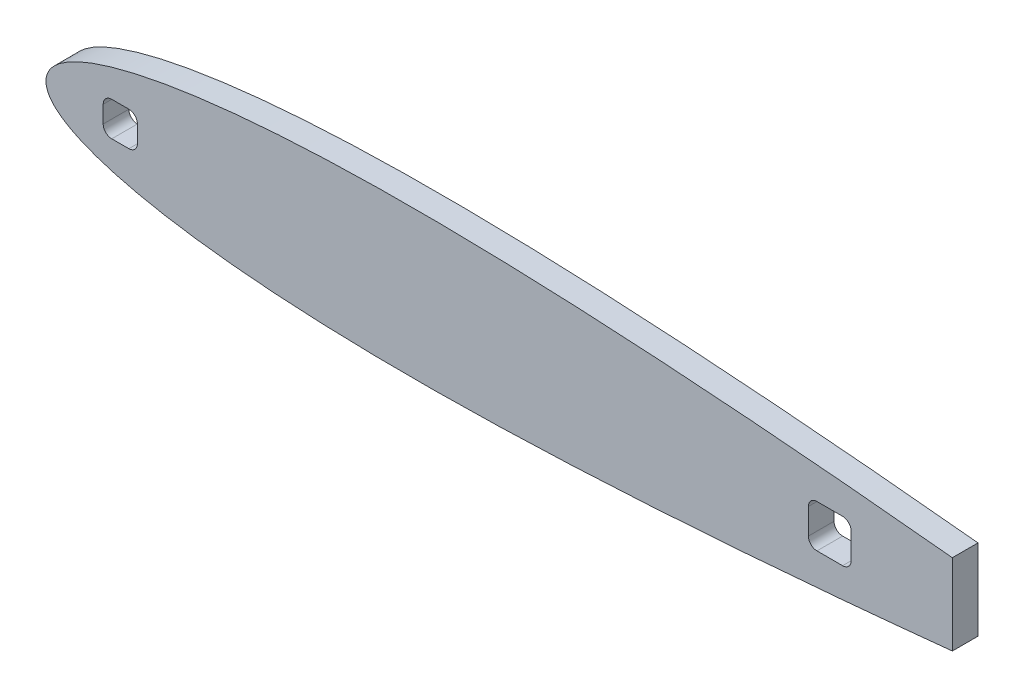
SolidWorks part; units mm, degrees
ref_plane "Plano frontal" through (0, 0, 0) normal (0, 0, 1) x (1, 0, 0)
ref_plane "Plano superior" through (0, 0, 0) normal (0, 1, 0) x (1, 0, 0)
ref_plane "Plano direito" through (0, 0, 0) normal (1, 0, 0) x (0, 0, -1)
curve "2"
  spline degree 3 poles (288.183, -0.2492, 0) (291.6672, 0, 0) (288.183, 0.2492, 0) (287.1244, 0.4014, 0) (286.6168, 0.4717, 0) (285.7832, 0.5886, 0) (284.6138, 0.7512, 0) (283.1169, 0.9577, 0) (281.2938, 1.2084, 0) (279.1495, 1.5004, 0) (276.6888, 1.832, 0) (273.9176, 2.2016, 0) (270.8422, 2.6067, 0) (267.47, 3.0454, 0) (263.8086, 3.5141, 0) (259.8667, 4.0116, 0) (255.6534, 4.5345, 0) (251.1787, 5.08, 0) (246.453, 5.6458, 0) (241.4874, 6.2288, 0) (236.2932, 6.8256, 0) (230.8828, 7.4346, 0) (225.2688, 8.0516, 0) (219.4645, 8.6747, 0) (213.483, 9.2996, 0) (207.3387, 9.9251, 0) (201.0457, 10.5464, 0) (194.6188, 11.1616, 0) (188.0729, 11.7663, 0) (181.4234, 12.3586, 0) (174.6858, 12.9335, 0) (167.8757, 13.4886, 0) (161.0093, 14.0203, 0) (154.1024, 14.5243, 0) (147.1712, 14.9974, 0) (140.232, 15.4359, 0) (133.3008, 15.8355, 0) (126.394, 16.193, 0) (119.5274, 16.5047, 0) (112.7172, 16.7669, 0) (105.9794, 16.9769, 0) (99.3298, 17.1307, 0) (92.7837, 17.2258, 0) (86.3563, 17.2595, 0) (80.0629, 17.2297, 0) (73.918, 17.1352, 0) (67.9362, 16.973, 0) (62.1311, 16.7439, 0) (56.5165, 16.4463, 0) (51.1054, 16.0809, 0) (45.9104, 15.6479, 0) (40.9437, 15.148, 0) (36.2169, 14.5831, 0) (31.7407, 13.9556, 0) (27.5258, 13.2665, 0) (23.5819, 12.5195, 0) (19.9179, 11.7171, 0) (16.5425, 10.8622, 0) (13.4631, 9.9587, 0) (10.6866, 9.0094, 0) (8.2187, 8.0177, 0) (6.0645, 6.9865, 0) (4.228, 5.9178, 0) (2.7114, 4.8135, 0) (1.5175, 3.6719, 0) (0.6493, 2.4895, 0) (0.1185, 1.2608, 0) (-0.0578, 0, 0) (0.1185, -1.2608, 0) (0.6493, -2.4895, 0) (1.5175, -3.6719, 0) (2.7114, -4.8135, 0) (4.228, -5.9178, 0) (6.0645, -6.9865, 0) (8.2187, -8.0177, 0) (10.6866, -9.0094, 0) (13.4631, -9.9587, 0) (16.5425, -10.8622, 0) (19.9179, -11.7171, 0) (23.5819, -12.5195, 0) (27.5258, -13.2665, 0) (31.7407, -13.9556, 0) (36.2169, -14.5831, 0) (40.9437, -15.148, 0) (45.9104, -15.6479, 0) (51.1054, -16.0809, 0) (56.5165, -16.4463, 0) (62.1311, -16.7439, 0) (67.9362, -16.973, 0) (73.918, -17.1352, 0) (80.0629, -17.2297, 0) (86.3563, -17.2595, 0) (92.7837, -17.2258, 0) (99.3298, -17.1307, 0) (105.9794, -16.9769, 0) (112.7172, -16.7669, 0) (119.5274, -16.5047, 0) (126.394, -16.193, 0) (133.3008, -15.8355, 0) (140.232, -15.4359, 0) (147.1712, -14.9974, 0) (154.1024, -14.5243, 0) (161.0093, -14.0203, 0) (167.8757, -13.4886, 0) (174.6858, -12.9335, 0) (181.4234, -12.3586, 0) (188.0729, -11.7663, 0) (194.6188, -11.1616, 0) (201.0457, -10.5464, 0) (207.3387, -9.9251, 0) (213.483, -9.2996, 0) (219.4645, -8.6747, 0) (225.2688, -8.0516, 0) (230.8828, -7.4346, 0) (236.2932, -6.8256, 0) (241.4874, -6.2288, 0) (246.453, -5.6458, 0) (251.1787, -5.08, 0) (255.6534, -4.5345, 0) (259.8667, -4.0116, 0) (263.8086, -3.5141, 0) (267.47, -3.0454, 0) (270.8422, -2.6067, 0) (273.9176, -2.2016, 0) (276.6888, -1.832, 0) (279.1495, -1.5004, 0) (281.2938, -1.2084, 0) (283.1169, -0.9577, 0) (284.6138, -0.7512, 0) (285.7832, -0.5886, 0) (286.6168, -0.4717, 0) (287.1244, -0.4014, 0) (288.183, -0.2492, 0) (291.6672, 0, 0) (288.183, 0.2492, 0) knots -0.00555 -0.004691 -0.004405 0 0.004405 0.004691 0.00555 0.00698 0.008976 0.011535 0.014649 0.018312 0.022515 0.027248 0.032498 0.038254 0.044502 0.051227 0.058413 0.066043 0.074099 0.082562 0.091412 0.100627 0.110187 0.120068 0.130247 0.140701 0.151404 0.162332 0.173459 0.184758 0.196204 0.207769 0.219426 0.231148 0.242906 0.254675 0.266426 0.278132 0.289766 0.301302 0.312712 0.323969 0.33505 0.345929 0.356581 0.366982 0.37711 0.386942 0.396458 0.405637 0.414459 0.422907 0.430963 0.438612 0.445838 0.45263 0.458976 0.464866 0.470294 0.475255 0.479749 0.483781 0.487363 0.490516 0.493279 0.495712 0.49791 0.5 0.50209 0.504288 0.506721 0.509484 0.512637 0.516219 0.520251 0.524745 0.529706 0.535134 0.541024 0.54737 0.554162 0.561388 0.569037 0.577093 0.585541 0.594363 0.603542 0.613058 0.62289 0.633018 0.643419 0.654071 0.66495 0.676031 0.687288 0.698698 0.710234 0.721868 0.733574 0.745325 0.757094 0.768852 0.780574 0.792231 0.803796 0.815242 0.826541 0.837668 0.848596 0.859299 0.869753 0.879932 0.889813 0.899373 0.908588 0.917438 0.925901 0.933957 0.941587 0.948773 0.955498 0.961746 0.967502 0.972752 0.977485 0.981688 0.985351 0.988465 0.991024 0.99302 0.99445 0.995309 0.995595 1 1.004405 1.004691 1.00555 periodic
curve "3"
  spline degree 3 poles (285.8178, -0.2472, 0) (289.2733, 0, 0) (285.8178, 0.2472, 0) (284.7679, 0.3981, 0) (284.2644, 0.4678, 0) (283.4377, 0.5838, 0) (282.2778, 0.7451, 0) (280.7932, 0.9499, 0) (278.9851, 1.1985, 0) (276.8584, 1.4881, 0) (274.4179, 1.8169, 0) (271.6694, 2.1836, 0) (268.6193, 2.5853, 0) (265.2747, 3.0204, 0) (261.6434, 3.4852, 0) (257.7338, 3.9787, 0) (253.5551, 4.4973, 0) (249.1172, 5.0383, 0) (244.4303, 5.5995, 0) (239.5054, 6.1777, 0) (234.3538, 6.7696, 0) (228.9879, 7.3736, 0) (223.4199, 7.9855, 0) (217.6632, 8.6035, 0) (211.7309, 9.2233, 0) (205.637, 9.8437, 0) (199.3956, 10.4599, 0) (193.0214, 11.07, 0) (186.5293, 11.6697, 0) (179.9344, 12.2571, 0) (173.2521, 12.8274, 0) (166.4979, 13.3779, 0) (159.6878, 13.9052, 0) (152.8376, 14.4051, 0) (145.9633, 14.8743, 0) (139.0811, 15.3092, 0) (132.2068, 15.7055, 0) (125.3566, 16.0601, 0) (118.5464, 16.3692, 0) (111.7921, 16.6293, 0) (105.1096, 16.8375, 0) (98.5145, 16.9901, 0) (92.0222, 17.0845, 0) (85.6476, 17.1179, 0) (79.4058, 17.0883, 0) (73.3113, 16.9946, 0) (67.3786, 16.8337, 0) (61.6212, 16.6065, 0) (56.0527, 16.3113, 0) (50.6859, 15.9489, 0) (45.5336, 15.5194, 0) (40.6077, 15.0237, 0) (35.9196, 14.4634, 0) (31.4802, 13.841, 0) (27.2999, 13.1577, 0) (23.3883, 12.4167, 0) (19.7544, 11.6209, 0) (16.4067, 10.7731, 0) (13.3526, 9.8769, 0) (10.5989, 8.9355, 0) (8.1513, 7.9519, 0) (6.0147, 6.9291, 0) (4.1933, 5.8692, 0) (2.6891, 4.774, 0) (1.5051, 3.6417, 0) (0.644, 2.4691, 0) (0.1176, 1.2504, 0) (-0.0573, 0, 0) (0.1176, -1.2504, 0) (0.644, -2.4691, 0) (1.5051, -3.6417, 0) (2.6891, -4.774, 0) (4.1933, -5.8692, 0) (6.0147, -6.9291, 0) (8.1513, -7.9519, 0) (10.5989, -8.9355, 0) (13.3526, -9.8769, 0) (16.4067, -10.7731, 0) (19.7544, -11.6209, 0) (23.3883, -12.4167, 0) (27.2999, -13.1577, 0) (31.4802, -13.841, 0) (35.9196, -14.4634, 0) (40.6077, -15.0237, 0) (45.5336, -15.5194, 0) (50.6859, -15.9489, 0) (56.0527, -16.3113, 0) (61.6212, -16.6065, 0) (67.3786, -16.8337, 0) (73.3113, -16.9946, 0) (79.4058, -17.0883, 0) (85.6476, -17.1179, 0) (92.0222, -17.0845, 0) (98.5145, -16.9901, 0) (105.1096, -16.8375, 0) (111.7921, -16.6293, 0) (118.5464, -16.3692, 0) (125.3566, -16.0601, 0) (132.2068, -15.7055, 0) (139.0811, -15.3092, 0) (145.9633, -14.8743, 0) (152.8376, -14.4051, 0) (159.6878, -13.9052, 0) (166.4979, -13.3779, 0) (173.2521, -12.8274, 0) (179.9344, -12.2571, 0) (186.5293, -11.6697, 0) (193.0214, -11.07, 0) (199.3956, -10.4599, 0) (205.637, -9.8437, 0) (211.7309, -9.2233, 0) (217.6632, -8.6035, 0) (223.4199, -7.9855, 0) (228.9879, -7.3736, 0) (234.3538, -6.7696, 0) (239.5054, -6.1777, 0) (244.4303, -5.5995, 0) (249.1172, -5.0383, 0) (253.5551, -4.4973, 0) (257.7338, -3.9787, 0) (261.6434, -3.4852, 0) (265.2747, -3.0204, 0) (268.6193, -2.5853, 0) (271.6694, -2.1836, 0) (274.4179, -1.8169, 0) (276.8584, -1.4881, 0) (278.9851, -1.1985, 0) (280.7932, -0.9499, 0) (282.2778, -0.7451, 0) (283.4377, -0.5838, 0) (284.2644, -0.4678, 0) (284.7679, -0.3981, 0) (285.8178, -0.2472, 0) (289.2733, 0, 0) (285.8178, 0.2472, 0) knots -0.00555 -0.004691 -0.004405 0 0.004405 0.004691 0.00555 0.00698 0.008976 0.011535 0.014649 0.018312 0.022515 0.027248 0.032498 0.038254 0.044502 0.051227 0.058413 0.066043 0.074099 0.082562 0.091412 0.100627 0.110187 0.120068 0.130247 0.140701 0.151404 0.162332 0.173459 0.184758 0.196204 0.207769 0.219426 0.231148 0.242906 0.254675 0.266426 0.278132 0.289766 0.301302 0.312712 0.323969 0.33505 0.345929 0.356581 0.366982 0.37711 0.386942 0.396458 0.405637 0.414459 0.422907 0.430963 0.438612 0.445838 0.45263 0.458976 0.464866 0.470294 0.475255 0.479749 0.483781 0.487363 0.490516 0.493279 0.495712 0.49791 0.5 0.50209 0.504288 0.506721 0.509484 0.512637 0.516219 0.520251 0.524745 0.529706 0.535134 0.541024 0.54737 0.554162 0.561388 0.569037 0.577093 0.585541 0.594363 0.603542 0.613058 0.62289 0.633018 0.643419 0.654071 0.66495 0.676031 0.687288 0.698698 0.710234 0.721868 0.733574 0.745325 0.757094 0.768852 0.780574 0.792231 0.803796 0.815242 0.826541 0.837668 0.848596 0.859299 0.869753 0.879932 0.889813 0.899373 0.908588 0.917438 0.925901 0.933957 0.941587 0.948773 0.955498 0.961746 0.967502 0.972752 0.977485 0.981688 0.985351 0.988465 0.991024 0.99302 0.99445 0.995309 0.995595 1 1.004405 1.004691 1.00555 periodic
sketch "2-3" plane through (0, 0, 0) normal (0, 0, 1) x (1, 0, 0)
  line L0 (287.6, 0) -> (289.98, 0) construction
  spline S0 degree 3 poles (285.8178, -0.2472) (289.2733, 0) (285.8178, 0.2472) (284.7679, 0.3981) (284.2644, 0.4678) (283.4377, 0.5838) (282.2778, 0.7451) (280.7932, 0.9499) (278.9851, 1.1985) (276.8584, 1.4881) (274.4179, 1.8169) (271.6694, 2.1836) (268.6193, 2.5853) (265.2747, 3.0204) (261.6434, 3.4852) (257.7338, 3.9787) (253.5551, 4.4973) (249.1172, 5.0383) (244.4303, 5.5995) (239.5054, 6.1777) (234.3538, 6.7696) (228.9879, 7.3736) (223.4199, 7.9855) (217.6632, 8.6035) (211.7309, 9.2233) (205.637, 9.8437) (199.3956, 10.4599) (193.0214, 11.07) (186.5293, 11.6697) (179.9344, 12.2571) (173.2521, 12.8274) (166.4979, 13.3779) (159.6878, 13.9052) (152.8376, 14.4051) (145.9633, 14.8743) (139.0811, 15.3092) (132.2068, 15.7055) (125.3566, 16.0601) (118.5464, 16.3692) (111.7921, 16.6293) (105.1096, 16.8375) (98.5145, 16.9901) (92.0222, 17.0845) (85.6476, 17.1179) (79.4058, 17.0883) (73.3113, 16.9946) (67.3786, 16.8337) (61.6212, 16.6065) (56.0527, 16.3113) (50.6859, 15.9489) (45.5336, 15.5194) (40.6077, 15.0237) (35.9196, 14.4634) (31.4802, 13.841) (27.2999, 13.1577) (23.3883, 12.4167) (19.7544, 11.6209) (16.4067, 10.7731) (13.3526, 9.8769) (10.5989, 8.9355) (8.1513, 7.9519) (6.0147, 6.9291) (4.1933, 5.8692) (2.6891, 4.774) (1.5051, 3.6417) (0.644, 2.4691) (0.1176, 1.2504) (-0.0573, 0) (0.1176, -1.2504) (0.644, -2.4691) (1.5051, -3.6417) (2.6891, -4.774) (4.1933, -5.8692) (6.0147, -6.9291) (8.1513, -7.9519) (10.5989, -8.9355) (13.3526, -9.8769) (16.4067, -10.7731) (19.7544, -11.6209) (23.3883, -12.4167) (27.2999, -13.1577) (31.4802, -13.841) (35.9196, -14.4634) (40.6077, -15.0237) (45.5336, -15.5194) (50.6859, -15.9489) (56.0527, -16.3113) (61.6212, -16.6065) (67.3786, -16.8337) (73.3113, -16.9946) (79.4058, -17.0883) (85.6476, -17.1179) (92.0222, -17.0845) (98.5145, -16.9901) (105.1096, -16.8375) (111.7921, -16.6293) (118.5464, -16.3692) (125.3566, -16.0601) (132.2068, -15.7055) (139.0811, -15.3092) (145.9633, -14.8743) (152.8376, -14.4051) (159.6878, -13.9052) (166.4979, -13.3779) (173.2521, -12.8274) (179.9344, -12.2571) (186.5293, -11.6697) (193.0214, -11.07) (199.3956, -10.4599) (205.637, -9.8437) (211.7309, -9.2233) (217.6632, -8.6035) (223.4199, -7.9855) (228.9879, -7.3736) (234.3538, -6.7696) (239.5054, -6.1777) (244.4303, -5.5995) (249.1172, -5.0383) (253.5551, -4.4973) (257.7338, -3.9787) (261.6434, -3.4852) (265.2747, -3.0204) (268.6193, -2.5853) (271.6694, -2.1836) (274.4179, -1.8169) (276.8584, -1.4881) (278.9851, -1.1985) (280.7932, -0.9499) (282.2778, -0.7451) (283.4377, -0.5838) (284.2644, -0.4678) (284.7679, -0.3981) (285.8178, -0.2472) (289.2733, 0) (285.8178, 0.2472) knots -0.00555 -0.004691 -0.004405 0 0.004405 0.004691 0.00555 0.00698 0.008976 0.011535 0.014649 0.018312 0.022515 0.027248 0.032498 0.038254 0.044502 0.051227 0.058413 0.066043 0.074099 0.082562 0.091412 0.100627 0.110187 0.120068 0.130247 0.140701 0.151404 0.162332 0.173459 0.184758 0.196204 0.207769 0.219426 0.231148 0.242906 0.254675 0.266426 0.278132 0.289766 0.301302 0.312712 0.323969 0.33505 0.345929 0.356581 0.366982 0.37711 0.386942 0.396458 0.405637 0.414459 0.422907 0.430963 0.438612 0.445838 0.45263 0.458976 0.464866 0.470294 0.475255 0.479749 0.483781 0.487363 0.490516 0.493279 0.495712 0.49791 0.5 0.50209 0.504288 0.506721 0.509484 0.512637 0.516219 0.520251 0.524745 0.529706 0.535134 0.541024 0.54737 0.554162 0.561388 0.569037 0.577093 0.585541 0.594363 0.603542 0.613058 0.62289 0.633018 0.643419 0.654071 0.66495 0.676031 0.687288 0.698698 0.710234 0.721868 0.733574 0.745325 0.757094 0.768852 0.780574 0.792231 0.803796 0.815242 0.826541 0.837668 0.848596 0.859299 0.869753 0.879932 0.889813 0.899373 0.908588 0.917438 0.925901 0.933957 0.941587 0.948773 0.955498 0.961746 0.967502 0.972752 0.977485 0.981688 0.985351 0.988465 0.991024 0.99302 0.99445 0.995309 0.995595 1 1.004405 1.004691 1.00555 only from (287.6, 0) to (287.6, 0) construction
  spline S1 degree 3 poles (288.183, -0.2492) (291.6672, 0) (288.183, 0.2492) (287.1244, 0.4014) (286.6168, 0.4717) (285.7832, 0.5886) (284.6138, 0.7512) (283.1169, 0.9577) (281.2938, 1.2084) (279.1495, 1.5004) (276.6888, 1.832) (273.9176, 2.2016) (270.8422, 2.6067) (267.47, 3.0454) (263.8086, 3.5141) (259.8667, 4.0116) (255.6534, 4.5345) (251.1787, 5.08) (246.453, 5.6458) (241.4874, 6.2288) (236.2932, 6.8256) (230.8828, 7.4346) (225.2688, 8.0516) (219.4645, 8.6747) (213.483, 9.2996) (207.3387, 9.9251) (201.0457, 10.5464) (194.6188, 11.1616) (188.0729, 11.7663) (181.4234, 12.3586) (174.6858, 12.9335) (167.8757, 13.4886) (161.0093, 14.0203) (154.1024, 14.5243) (147.1712, 14.9974) (140.232, 15.4359) (133.3008, 15.8355) (126.394, 16.193) (119.5274, 16.5047) (112.7172, 16.7669) (105.9794, 16.9769) (99.3298, 17.1307) (92.7837, 17.2258) (86.3563, 17.2595) (80.0629, 17.2297) (73.918, 17.1352) (67.9362, 16.973) (62.1311, 16.7439) (56.5165, 16.4463) (51.1054, 16.0809) (45.9104, 15.6479) (40.9437, 15.148) (36.2169, 14.5831) (31.7407, 13.9556) (27.5258, 13.2665) (23.5819, 12.5195) (19.9179, 11.7171) (16.5425, 10.8622) (13.4631, 9.9587) (10.6866, 9.0094) (8.2187, 8.0177) (6.0645, 6.9865) (4.228, 5.9178) (2.7114, 4.8135) (1.5175, 3.6719) (0.6493, 2.4895) (0.1185, 1.2608) (-0.0578, 0) (0.1185, -1.2608) (0.6493, -2.4895) (1.5175, -3.6719) (2.7114, -4.8135) (4.228, -5.9178) (6.0645, -6.9865) (8.2187, -8.0177) (10.6866, -9.0094) (13.4631, -9.9587) (16.5425, -10.8622) (19.9179, -11.7171) (23.5819, -12.5195) (27.5258, -13.2665) (31.7407, -13.9556) (36.2169, -14.5831) (40.9437, -15.148) (45.9104, -15.6479) (51.1054, -16.0809) (56.5165, -16.4463) (62.1311, -16.7439) (67.9362, -16.973) (73.918, -17.1352) (80.0629, -17.2297) (86.3563, -17.2595) (92.7837, -17.2258) (99.3298, -17.1307) (105.9794, -16.9769) (112.7172, -16.7669) (119.5274, -16.5047) (126.394, -16.193) (133.3008, -15.8355) (140.232, -15.4359) (147.1712, -14.9974) (154.1024, -14.5243) (161.0093, -14.0203) (167.8757, -13.4886) (174.6858, -12.9335) (181.4234, -12.3586) (188.0729, -11.7663) (194.6188, -11.1616) (201.0457, -10.5464) (207.3387, -9.9251) (213.483, -9.2996) (219.4645, -8.6747) (225.2688, -8.0516) (230.8828, -7.4346) (236.2932, -6.8256) (241.4874, -6.2288) (246.453, -5.6458) (251.1787, -5.08) (255.6534, -4.5345) (259.8667, -4.0116) (263.8086, -3.5141) (267.47, -3.0454) (270.8422, -2.6067) (273.9176, -2.2016) (276.6888, -1.832) (279.1495, -1.5004) (281.2938, -1.2084) (283.1169, -0.9577) (284.6138, -0.7512) (285.7832, -0.5886) (286.6168, -0.4717) (287.1244, -0.4014) (288.183, -0.2492) (291.6672, 0) (288.183, 0.2492) knots -0.00555 -0.004691 -0.004405 0 0.004405 0.004691 0.00555 0.00698 0.008976 0.011535 0.014649 0.018312 0.022515 0.027248 0.032498 0.038254 0.044502 0.051227 0.058413 0.066043 0.074099 0.082562 0.091412 0.100627 0.110187 0.120068 0.130247 0.140701 0.151404 0.162332 0.173459 0.184758 0.196204 0.207769 0.219426 0.231148 0.242906 0.254675 0.266426 0.278132 0.289766 0.301302 0.312712 0.323969 0.33505 0.345929 0.356581 0.366982 0.37711 0.386942 0.396458 0.405637 0.414459 0.422907 0.430963 0.438612 0.445838 0.45263 0.458976 0.464866 0.470294 0.475255 0.479749 0.483781 0.487363 0.490516 0.493279 0.495712 0.49791 0.5 0.50209 0.504288 0.506721 0.509484 0.512637 0.516219 0.520251 0.524745 0.529706 0.535134 0.541024 0.54737 0.554162 0.561388 0.569037 0.577093 0.585541 0.594363 0.603542 0.613058 0.62289 0.633018 0.643419 0.654071 0.66495 0.676031 0.687288 0.698698 0.710234 0.721868 0.733574 0.745325 0.757094 0.768852 0.780574 0.792231 0.803796 0.815242 0.826541 0.837668 0.848596 0.859299 0.869753 0.879932 0.889813 0.899373 0.908588 0.917438 0.925901 0.933957 0.941587 0.948773 0.955498 0.961746 0.967502 0.972752 0.977485 0.981688 0.985351 0.988465 0.991024 0.99302 0.99445 0.995309 0.995595 1 1.004405 1.004691 1.00555 only from (289.98, 0) to (289.98, 0) construction
  spline S2 degree 3 poles (285.8178, -0.2472) (289.2733, 0) (285.8178, 0.2472) (284.7679, 0.3981) (284.2644, 0.4678) (283.4377, 0.5838) (282.2778, 0.7451) (280.7932, 0.9499) (278.9851, 1.1985) (276.8584, 1.4881) (274.4179, 1.8169) (271.6694, 2.1836) (268.6193, 2.5853) (265.2747, 3.0204) (261.6434, 3.4852) (257.7338, 3.9787) (253.5551, 4.4973) (249.1172, 5.0383) (244.4303, 5.5995) (239.5054, 6.1777) (234.3538, 6.7696) (228.9879, 7.3736) (223.4199, 7.9855) (217.6632, 8.6035) (211.7309, 9.2233) (205.637, 9.8437) (199.3956, 10.4599) (193.0214, 11.07) (186.5293, 11.6697) (179.9344, 12.2571) (173.2521, 12.8274) (166.4979, 13.3779) (159.6878, 13.9052) (152.8376, 14.4051) (145.9633, 14.8743) (139.0811, 15.3092) (132.2068, 15.7055) (125.3566, 16.0601) (118.5464, 16.3692) (111.7921, 16.6293) (105.1096, 16.8375) (98.5145, 16.9901) (92.0222, 17.0845) (85.6476, 17.1179) (79.4058, 17.0883) (73.3113, 16.9946) (67.3786, 16.8337) (61.6212, 16.6065) (56.0527, 16.3113) (50.6859, 15.9489) (45.5336, 15.5194) (40.6077, 15.0237) (35.9196, 14.4634) (31.4802, 13.841) (27.2999, 13.1577) (23.3883, 12.4167) (19.7544, 11.6209) (16.4067, 10.7731) (13.3526, 9.8769) (10.5989, 8.9355) (8.1513, 7.9519) (6.0147, 6.9291) (4.1933, 5.8692) (2.6891, 4.774) (1.5051, 3.6417) (0.644, 2.4691) (0.1176, 1.2504) (-0.0573, 0) (0.1176, -1.2504) (0.644, -2.4691) (1.5051, -3.6417) (2.6891, -4.774) (4.1933, -5.8692) (6.0147, -6.9291) (8.1513, -7.9519) (10.5989, -8.9355) (13.3526, -9.8769) (16.4067, -10.7731) (19.7544, -11.6209) (23.3883, -12.4167) (27.2999, -13.1577) (31.4802, -13.841) (35.9196, -14.4634) (40.6077, -15.0237) (45.5336, -15.5194) (50.6859, -15.9489) (56.0527, -16.3113) (61.6212, -16.6065) (67.3786, -16.8337) (73.3113, -16.9946) (79.4058, -17.0883) (85.6476, -17.1179) (92.0222, -17.0845) (98.5145, -16.9901) (105.1096, -16.8375) (111.7921, -16.6293) (118.5464, -16.3692) (125.3566, -16.0601) (132.2068, -15.7055) (139.0811, -15.3092) (145.9633, -14.8743) (152.8376, -14.4051) (159.6878, -13.9052) (166.4979, -13.3779) (173.2521, -12.8274) (179.9344, -12.2571) (186.5293, -11.6697) (193.0214, -11.07) (199.3956, -10.4599) (205.637, -9.8437) (211.7309, -9.2233) (217.6632, -8.6035) (223.4199, -7.9855) (228.9879, -7.3736) (234.3538, -6.7696) (239.5054, -6.1777) (244.4303, -5.5995) (249.1172, -5.0383) (253.5551, -4.4973) (257.7338, -3.9787) (261.6434, -3.4852) (265.2747, -3.0204) (268.6193, -2.5853) (271.6694, -2.1836) (274.4179, -1.8169) (276.8584, -1.4881) (278.9851, -1.1985) (280.7932, -0.9499) (282.2778, -0.7451) (283.4377, -0.5838) (284.2644, -0.4678) (284.7679, -0.3981) (285.8178, -0.2472) (289.2733, 0) (285.8178, 0.2472) knots -0.00555 -0.004691 -0.004405 0 0.004405 0.004691 0.00555 0.00698 0.008976 0.011535 0.014649 0.018312 0.022515 0.027248 0.032498 0.038254 0.044502 0.051227 0.058413 0.066043 0.074099 0.082562 0.091412 0.100627 0.110187 0.120068 0.130247 0.140701 0.151404 0.162332 0.173459 0.184758 0.196204 0.207769 0.219426 0.231148 0.242906 0.254675 0.266426 0.278132 0.289766 0.301302 0.312712 0.323969 0.33505 0.345929 0.356581 0.366982 0.37711 0.386942 0.396458 0.405637 0.414459 0.422907 0.430963 0.438612 0.445838 0.45263 0.458976 0.464866 0.470294 0.475255 0.479749 0.483781 0.487363 0.490516 0.493279 0.495712 0.49791 0.5 0.50209 0.504288 0.506721 0.509484 0.512637 0.516219 0.520251 0.524745 0.529706 0.535134 0.541024 0.54737 0.554162 0.561388 0.569037 0.577093 0.585541 0.594363 0.603542 0.613058 0.62289 0.633018 0.643419 0.654071 0.66495 0.676031 0.687288 0.698698 0.710234 0.721868 0.733574 0.745325 0.757094 0.768852 0.780574 0.792231 0.803796 0.815242 0.826541 0.837668 0.848596 0.859299 0.869753 0.879932 0.889813 0.899373 0.908588 0.917438 0.925901 0.933957 0.941587 0.948773 0.955498 0.961746 0.967502 0.972752 0.977485 0.981688 0.985351 0.988465 0.991024 0.99302 0.99445 0.995309 0.995595 1 1.004405 1.004691 1.00555 only from (287.6, 0) to (287.6, 0)
  spline S3 degree 3 poles (288.183, -0.2492) (291.6672, 0) (288.183, 0.2492) (287.1244, 0.4014) (286.6168, 0.4717) (285.7832, 0.5886) (284.6138, 0.7512) (283.1169, 0.9577) (281.2938, 1.2084) (279.1495, 1.5004) (276.6888, 1.832) (273.9176, 2.2016) (270.8422, 2.6067) (267.47, 3.0454) (263.8086, 3.5141) (259.8667, 4.0116) (255.6534, 4.5345) (251.1787, 5.08) (246.453, 5.6458) (241.4874, 6.2288) (236.2932, 6.8256) (230.8828, 7.4346) (225.2688, 8.0516) (219.4645, 8.6747) (213.483, 9.2996) (207.3387, 9.9251) (201.0457, 10.5464) (194.6188, 11.1616) (188.0729, 11.7663) (181.4234, 12.3586) (174.6858, 12.9335) (167.8757, 13.4886) (161.0093, 14.0203) (154.1024, 14.5243) (147.1712, 14.9974) (140.232, 15.4359) (133.3008, 15.8355) (126.394, 16.193) (119.5274, 16.5047) (112.7172, 16.7669) (105.9794, 16.9769) (99.3298, 17.1307) (92.7837, 17.2258) (86.3563, 17.2595) (80.0629, 17.2297) (73.918, 17.1352) (67.9362, 16.973) (62.1311, 16.7439) (56.5165, 16.4463) (51.1054, 16.0809) (45.9104, 15.6479) (40.9437, 15.148) (36.2169, 14.5831) (31.7407, 13.9556) (27.5258, 13.2665) (23.5819, 12.5195) (19.9179, 11.7171) (16.5425, 10.8622) (13.4631, 9.9587) (10.6866, 9.0094) (8.2187, 8.0177) (6.0645, 6.9865) (4.228, 5.9178) (2.7114, 4.8135) (1.5175, 3.6719) (0.6493, 2.4895) (0.1185, 1.2608) (-0.0578, 0) (0.1185, -1.2608) (0.6493, -2.4895) (1.5175, -3.6719) (2.7114, -4.8135) (4.228, -5.9178) (6.0645, -6.9865) (8.2187, -8.0177) (10.6866, -9.0094) (13.4631, -9.9587) (16.5425, -10.8622) (19.9179, -11.7171) (23.5819, -12.5195) (27.5258, -13.2665) (31.7407, -13.9556) (36.2169, -14.5831) (40.9437, -15.148) (45.9104, -15.6479) (51.1054, -16.0809) (56.5165, -16.4463) (62.1311, -16.7439) (67.9362, -16.973) (73.918, -17.1352) (80.0629, -17.2297) (86.3563, -17.2595) (92.7837, -17.2258) (99.3298, -17.1307) (105.9794, -16.9769) (112.7172, -16.7669) (119.5274, -16.5047) (126.394, -16.193) (133.3008, -15.8355) (140.232, -15.4359) (147.1712, -14.9974) (154.1024, -14.5243) (161.0093, -14.0203) (167.8757, -13.4886) (174.6858, -12.9335) (181.4234, -12.3586) (188.0729, -11.7663) (194.6188, -11.1616) (201.0457, -10.5464) (207.3387, -9.9251) (213.483, -9.2996) (219.4645, -8.6747) (225.2688, -8.0516) (230.8828, -7.4346) (236.2932, -6.8256) (241.4874, -6.2288) (246.453, -5.6458) (251.1787, -5.08) (255.6534, -4.5345) (259.8667, -4.0116) (263.8086, -3.5141) (267.47, -3.0454) (270.8422, -2.6067) (273.9176, -2.2016) (276.6888, -1.832) (279.1495, -1.5004) (281.2938, -1.2084) (283.1169, -0.9577) (284.6138, -0.7512) (285.7832, -0.5886) (286.6168, -0.4717) (287.1244, -0.4014) (288.183, -0.2492) (291.6672, 0) (288.183, 0.2492) knots -0.00555 -0.004691 -0.004405 0 0.004405 0.004691 0.00555 0.00698 0.008976 0.011535 0.014649 0.018312 0.022515 0.027248 0.032498 0.038254 0.044502 0.051227 0.058413 0.066043 0.074099 0.082562 0.091412 0.100627 0.110187 0.120068 0.130247 0.140701 0.151404 0.162332 0.173459 0.184758 0.196204 0.207769 0.219426 0.231148 0.242906 0.254675 0.266426 0.278132 0.289766 0.301302 0.312712 0.323969 0.33505 0.345929 0.356581 0.366982 0.37711 0.386942 0.396458 0.405637 0.414459 0.422907 0.430963 0.438612 0.445838 0.45263 0.458976 0.464866 0.470294 0.475255 0.479749 0.483781 0.487363 0.490516 0.493279 0.495712 0.49791 0.5 0.50209 0.504288 0.506721 0.509484 0.512637 0.516219 0.520251 0.524745 0.529706 0.535134 0.541024 0.54737 0.554162 0.561388 0.569037 0.577093 0.585541 0.594363 0.603542 0.613058 0.62289 0.633018 0.643419 0.654071 0.66495 0.676031 0.687288 0.698698 0.710234 0.721868 0.733574 0.745325 0.757094 0.768852 0.780574 0.792231 0.803796 0.815242 0.826541 0.837668 0.848596 0.859299 0.869753 0.879932 0.889813 0.899373 0.908588 0.917438 0.925901 0.933957 0.941587 0.948773 0.955498 0.961746 0.967502 0.972752 0.977485 0.981688 0.985351 0.988465 0.991024 0.99302 0.99445 0.995309 0.995595 1 1.004405 1.004691 1.00555 only from (289.98, 0) to (289.98, 0)
  dimension "D1" = 2.38
sketch "Esboço2" plane through (0, 0, 0) normal (0, 0, 1) x (1, 0, 0)
  line L0 (289.98, 0) -> (211.98, 0) construction
  line L1 (289.98, 0) -> (183.3133, 0) construction
  line L2 (0, 0) -> (17.38, 0) construction
  line L3 (180.3133, -5) -> (186.3133, -5)
  line L4 (178.3133, -3) -> (178.3133, 3)
  line L5 (180.3133, 5) -> (186.3133, 5)
  line L6 (188.3133, -3) -> (188.3133, 3)
  line L7 (178.3133, -5) -> (188.3133, 5) construction
  line L8 (178.3133, 5) -> (188.3133, -5) construction
  line L9 (211.98, 9.4514) -> (211.98, -9.4514)
  line L10 (15.38, -4) -> (19.38, -4)
  line L11 (13.38, -2) -> (13.38, 2)
  line L12 (15.38, 4) -> (19.38, 4)
  line L13 (21.38, -2) -> (21.38, 2)
  line L14 (13.38, -4) -> (21.38, 4) construction
  line L15 (13.38, 4) -> (21.38, -4) construction
  arc A0 (211.98, 9.4514) -> (211.98, -9.4514) centre (217.4368, 0) ccw construction
  arc A3 (15.38, -4) -> (13.38, -2) centre (15.38, -2) cw
  arc A4 (19.38, -4) -> (21.38, -2) centre (19.38, -2) ccw
  arc A5 (19.38, 4) -> (21.38, 2) centre (19.38, 2) cw
  arc A6 (13.38, 2) -> (15.38, 4) centre (15.38, 2) cw
  arc A7 (180.3133, -5) -> (178.3133, -3) centre (180.3133, -3) cw
  arc A8 (186.3133, -5) -> (188.3133, -3) centre (186.3133, -3) ccw
  arc A9 (186.3133, 5) -> (188.3133, 3) centre (186.3133, 3) cw
  arc A10 (178.3133, 3) -> (180.3133, 5) centre (180.3133, 3) cw
  spline S0 degree 3 poles (288.183, -0.2492) (291.6672, 0) (288.183, 0.2492) (287.1244, 0.4014) (286.6168, 0.4717) (285.7832, 0.5886) (284.6138, 0.7512) (283.1169, 0.9577) (281.2938, 1.2084) (279.1495, 1.5004) (276.6888, 1.832) (273.9176, 2.2016) (270.8422, 2.6067) (267.47, 3.0454) (263.8086, 3.5141) (259.8667, 4.0116) (255.6534, 4.5345) (251.1787, 5.08) (246.453, 5.6458) (241.4874, 6.2288) (236.2932, 6.8256) (230.8828, 7.4346) (225.2688, 8.0516) (219.4645, 8.6747) (213.483, 9.2996) (207.3387, 9.9251) (201.0457, 10.5464) (194.6188, 11.1616) (188.0729, 11.7663) (181.4234, 12.3586) (174.6858, 12.9335) (167.8757, 13.4886) (161.0093, 14.0203) (154.1024, 14.5243) (147.1712, 14.9974) (140.232, 15.4359) (133.3008, 15.8355) (126.394, 16.193) (119.5274, 16.5047) (112.7172, 16.7669) (105.9794, 16.9769) (99.3298, 17.1307) (92.7837, 17.2258) (86.3563, 17.2595) (80.0629, 17.2297) (73.918, 17.1352) (67.9362, 16.973) (62.1311, 16.7439) (56.5165, 16.4463) (51.1054, 16.0809) (45.9104, 15.6479) (40.9437, 15.148) (36.2169, 14.5831) (31.7407, 13.9556) (27.5258, 13.2665) (23.5819, 12.5195) (19.9179, 11.7171) (16.5425, 10.8622) (13.4631, 9.9587) (10.6866, 9.0094) (8.2187, 8.0177) (6.0645, 6.9865) (4.228, 5.9178) (2.7114, 4.8135) (1.5175, 3.6719) (0.6493, 2.4895) (0.1185, 1.2608) (-0.0578, 0) (0.1185, -1.2608) (0.6493, -2.4895) (1.5175, -3.6719) (2.7114, -4.8135) (4.228, -5.9178) (6.0645, -6.9865) (8.2187, -8.0177) (10.6866, -9.0094) (13.4631, -9.9587) (16.5425, -10.8622) (19.9179, -11.7171) (23.5819, -12.5195) (27.5258, -13.2665) (31.7407, -13.9556) (36.2169, -14.5831) (40.9437, -15.148) (45.9104, -15.6479) (51.1054, -16.0809) (56.5165, -16.4463) (62.1311, -16.7439) (67.9362, -16.973) (73.918, -17.1352) (80.0629, -17.2297) (86.3563, -17.2595) (92.7837, -17.2258) (99.3298, -17.1307) (105.9794, -16.9769) (112.7172, -16.7669) (119.5274, -16.5047) (126.394, -16.193) (133.3008, -15.8355) (140.232, -15.4359) (147.1712, -14.9974) (154.1024, -14.5243) (161.0093, -14.0203) (167.8757, -13.4886) (174.6858, -12.9335) (181.4234, -12.3586) (188.0729, -11.7663) (194.6188, -11.1616) (201.0457, -10.5464) (207.3387, -9.9251) (213.483, -9.2996) (219.4645, -8.6747) (225.2688, -8.0516) (230.8828, -7.4346) (236.2932, -6.8256) (241.4874, -6.2288) (246.453, -5.6458) (251.1787, -5.08) (255.6534, -4.5345) (259.8667, -4.0116) (263.8086, -3.5141) (267.47, -3.0454) (270.8422, -2.6067) (273.9176, -2.2016) (276.6888, -1.832) (279.1495, -1.5004) (281.2938, -1.2084) (283.1169, -0.9577) (284.6138, -0.7512) (285.7832, -0.5886) (286.6168, -0.4717) (287.1244, -0.4014) (288.183, -0.2492) (291.6672, 0) (288.183, 0.2492) knots -0.00555 -0.004691 -0.004405 0 0.004405 0.004691 0.00555 0.00698 0.008976 0.011535 0.014649 0.018312 0.022515 0.027248 0.032498 0.038254 0.044502 0.051227 0.058413 0.066043 0.074099 0.082562 0.091412 0.100627 0.110187 0.120068 0.130247 0.140701 0.151404 0.162332 0.173459 0.184758 0.196204 0.207769 0.219426 0.231148 0.242906 0.254675 0.266426 0.278132 0.289766 0.301302 0.312712 0.323969 0.33505 0.345929 0.356581 0.366982 0.37711 0.386942 0.396458 0.405637 0.414459 0.422907 0.430963 0.438612 0.445838 0.45263 0.458976 0.464866 0.470294 0.475255 0.479749 0.483781 0.487363 0.490516 0.493279 0.495712 0.49791 0.5 0.50209 0.504288 0.506721 0.509484 0.512637 0.516219 0.520251 0.524745 0.529706 0.535134 0.541024 0.54737 0.554162 0.561388 0.569037 0.577093 0.585541 0.594363 0.603542 0.613058 0.62289 0.633018 0.643419 0.654071 0.66495 0.676031 0.687288 0.698698 0.710234 0.721868 0.733574 0.745325 0.757094 0.768852 0.780574 0.792231 0.803796 0.815242 0.826541 0.837668 0.848596 0.859299 0.869753 0.879932 0.889813 0.899373 0.908588 0.917438 0.925901 0.933957 0.941587 0.948773 0.955498 0.961746 0.967502 0.972752 0.977485 0.981688 0.985351 0.988465 0.991024 0.99302 0.99445 0.995309 0.995595 1 1.004405 1.004691 1.00555 only from (289.98, 0) to (289.98, 0) construction
  spline S1 degree 3 poles (288.183, -0.2492) (291.6672, 0) (288.183, 0.2492) (287.1244, 0.4014) (286.6168, 0.4717) (285.7832, 0.5886) (284.6138, 0.7512) (283.1169, 0.9577) (281.2938, 1.2084) (279.1495, 1.5004) (276.6888, 1.832) (273.9176, 2.2016) (270.8422, 2.6067) (267.47, 3.0454) (263.8086, 3.5141) (259.8667, 4.0116) (255.6534, 4.5345) (251.1787, 5.08) (246.453, 5.6458) (241.4874, 6.2288) (236.2932, 6.8256) (230.8828, 7.4346) (225.2688, 8.0516) (219.4645, 8.6747) (213.483, 9.2996) (207.3387, 9.9251) (201.0457, 10.5464) (194.6188, 11.1616) (188.0729, 11.7663) (181.4234, 12.3586) (174.6858, 12.9335) (167.8757, 13.4886) (161.0093, 14.0203) (154.1024, 14.5243) (147.1712, 14.9974) (140.232, 15.4359) (133.3008, 15.8355) (126.394, 16.193) (119.5274, 16.5047) (112.7172, 16.7669) (105.9794, 16.9769) (99.3298, 17.1307) (92.7837, 17.2258) (86.3563, 17.2595) (80.0629, 17.2297) (73.918, 17.1352) (67.9362, 16.973) (62.1311, 16.7439) (56.5165, 16.4463) (51.1054, 16.0809) (45.9104, 15.6479) (40.9437, 15.148) (36.2169, 14.5831) (31.7407, 13.9556) (27.5258, 13.2665) (23.5819, 12.5195) (19.9179, 11.7171) (16.5425, 10.8622) (13.4631, 9.9587) (10.6866, 9.0094) (8.2187, 8.0177) (6.0645, 6.9865) (4.228, 5.9178) (2.7114, 4.8135) (1.5175, 3.6719) (0.6493, 2.4895) (0.1185, 1.2608) (-0.0578, 0) (0.1185, -1.2608) (0.6493, -2.4895) (1.5175, -3.6719) (2.7114, -4.8135) (4.228, -5.9178) (6.0645, -6.9865) (8.2187, -8.0177) (10.6866, -9.0094) (13.4631, -9.9587) (16.5425, -10.8622) (19.9179, -11.7171) (23.5819, -12.5195) (27.5258, -13.2665) (31.7407, -13.9556) (36.2169, -14.5831) (40.9437, -15.148) (45.9104, -15.6479) (51.1054, -16.0809) (56.5165, -16.4463) (62.1311, -16.7439) (67.9362, -16.973) (73.918, -17.1352) (80.0629, -17.2297) (86.3563, -17.2595) (92.7837, -17.2258) (99.3298, -17.1307) (105.9794, -16.9769) (112.7172, -16.7669) (119.5274, -16.5047) (126.394, -16.193) (133.3008, -15.8355) (140.232, -15.4359) (147.1712, -14.9974) (154.1024, -14.5243) (161.0093, -14.0203) (167.8757, -13.4886) (174.6858, -12.9335) (181.4234, -12.3586) (188.0729, -11.7663) (194.6188, -11.1616) (201.0457, -10.5464) (207.3387, -9.9251) (213.483, -9.2996) (219.4645, -8.6747) (225.2688, -8.0516) (230.8828, -7.4346) (236.2932, -6.8256) (241.4874, -6.2288) (246.453, -5.6458) (251.1787, -5.08) (255.6534, -4.5345) (259.8667, -4.0116) (263.8086, -3.5141) (267.47, -3.0454) (270.8422, -2.6067) (273.9176, -2.2016) (276.6888, -1.832) (279.1495, -1.5004) (281.2938, -1.2084) (283.1169, -0.9577) (284.6138, -0.7512) (285.7832, -0.5886) (286.6168, -0.4717) (287.1244, -0.4014) (288.183, -0.2492) (291.6672, 0) (288.183, 0.2492) knots -0.00555 -0.004691 -0.004405 0 0.004405 0.004691 0.00555 0.00698 0.008976 0.011535 0.014649 0.018312 0.022515 0.027248 0.032498 0.038254 0.044502 0.051227 0.058413 0.066043 0.074099 0.082562 0.091412 0.100627 0.110187 0.120068 0.130247 0.140701 0.151404 0.162332 0.173459 0.184758 0.196204 0.207769 0.219426 0.231148 0.242906 0.254675 0.266426 0.278132 0.289766 0.301302 0.312712 0.323969 0.33505 0.345929 0.356581 0.366982 0.37711 0.386942 0.396458 0.405637 0.414459 0.422907 0.430963 0.438612 0.445838 0.45263 0.458976 0.464866 0.470294 0.475255 0.479749 0.483781 0.487363 0.490516 0.493279 0.495712 0.49791 0.5 0.50209 0.504288 0.506721 0.509484 0.512637 0.516219 0.520251 0.524745 0.529706 0.535134 0.541024 0.54737 0.554162 0.561388 0.569037 0.577093 0.585541 0.594363 0.603542 0.613058 0.62289 0.633018 0.643419 0.654071 0.66495 0.676031 0.687288 0.698698 0.710234 0.721868 0.733574 0.745325 0.757094 0.768852 0.780574 0.792231 0.803796 0.815242 0.826541 0.837668 0.848596 0.859299 0.869753 0.879932 0.889813 0.899373 0.908588 0.917438 0.925901 0.933957 0.941587 0.948773 0.955498 0.961746 0.967502 0.972752 0.977485 0.981688 0.985351 0.988465 0.991024 0.99302 0.99445 0.995309 0.995595 1 1.004405 1.004691 1.00555 only from (289.98, 0) to (289.98, 0)
  dimension "D9" = 2
  dimension "D1" = 78
  dimension "D2" = 106.6667
  dimension "D3" = 10
  dimension "D4" = 10
  dimension "D6" = 17.38
  dimension "D7" = 8
  dimension "D8" = 8
extrude "Ressalto-extrusão2" add sketch "Esboço2" along normal blind 6
